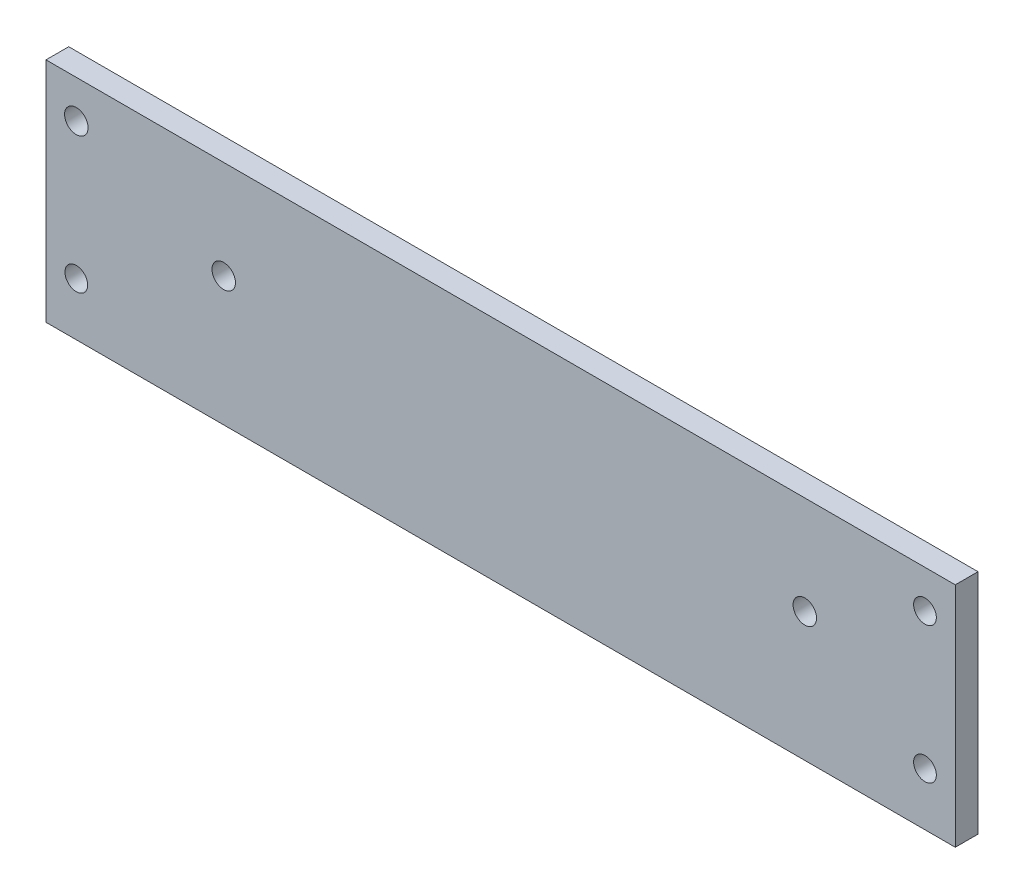
SolidWorks part; units mm, degrees
ref_plane "前视基准面" through (0, 0, 0) normal (0, 0, 1) x (1, 0, 0)
ref_plane "上视基准面" through (0, 0, 0) normal (0, 1, 0) x (1, 0, 0)
ref_plane "右视基准面" through (0, 0, 0) normal (1, 0, 0) x (0, 0, -1)
other "Configuration Table"
sketch "草图1" plane through (0, 0, 0) normal (0, 0, 1) x (1, 0, 0)
  line L1 (60, -15) -> (-60, -15)
  line L2 (60, -15) -> (60, 15)
  line L3 (60, 15) -> (-60, 15)
  line L4 (-60, -15) -> (-60, 15)
  line L5 (60, -15) -> (-60, 15) construction
  line L6 (60, 15) -> (-60, -15) construction
  point P0 (0, 0)
  dimension "D1" = 120
  dimension "D2" = 30
extrude "凸台-拉伸1" add sketch "草图1" along normal blind 3
sketch "草图3" plane through (0, 0, 0) normal (0, 0, -1) x (-1, 0, 0)
  line L2 (60, 15) -> (60, -15) construction
  line L3 (-60, 15) -> (60, 15) construction
  line L5 (-60, -15) -> (-60, 15) construction
  circle A0 centre (-56, 10) radius 1.5
  circle A1 centre (56, 10) radius 1.55
  dimension "D1" = 4
  dimension "D2" = 5
  dimension "D3" = 4
  dimension "D4" = 5
extrude "切除-拉伸2" cut sketch "草图3" against normal blind 10
sketch "草图4" plane through (0, 0, 3) normal (0, 0, 1) x (1, 0, 0)
  line L0 (0, 15) -> (0, 0) construction
  line L1 (60, 15) -> (-60, 15) construction
  line L2 (-60, -15) -> (60, -15) construction
  circle A0 centre (-26.25, -2) radius 1.55
  circle A1 centre (-26.25, -9) radius 1.55
  circle A2 centre (26.25, -9) radius 1.55
  circle A3 centre (26.25, -2) radius 1.55
  dimension "D1" = 3.1
  dimension "D2" = 3.1
  dimension "D5" = 6
  dimension "D3" = 26.25
  dimension "D4" = 26.25
  dimension "D6" = 13
sketch "草图5" plane through (0, 15, 0) normal (0, 1, 0) x (1, 0, 0)
  line L0 (0, 0) -> (0, -3) construction
  line L1 (60, -3) -> (-60, -3) construction
sketch "草图6" plane through (0, 0, 3) normal (0, 0, 1) x (1, 0, 0)
  line L0 (-56, 10) -> (-56, -8) construction
  line L1 (56, 10) -> (56, -8) construction
  circle A0 centre (-56, -8) radius 1.5
  circle A1 centre (56, -8) radius 1.5
  dimension "D1" = 3
  dimension "D2" = 18
extrude "切除-拉伸3" cut sketch "草图6" against normal blind 10
sketch "草图8" plane through (0, 0, 0) normal (0, 0, -1) x (-1, 0, 0)
  circle A0 centre (-40.1463, 2.02) radius 1.55
  circle A1 centre (36.5463, 2.02) radius 1.55
extrude "切除-拉伸4" cut sketch "草图8" against normal through all
